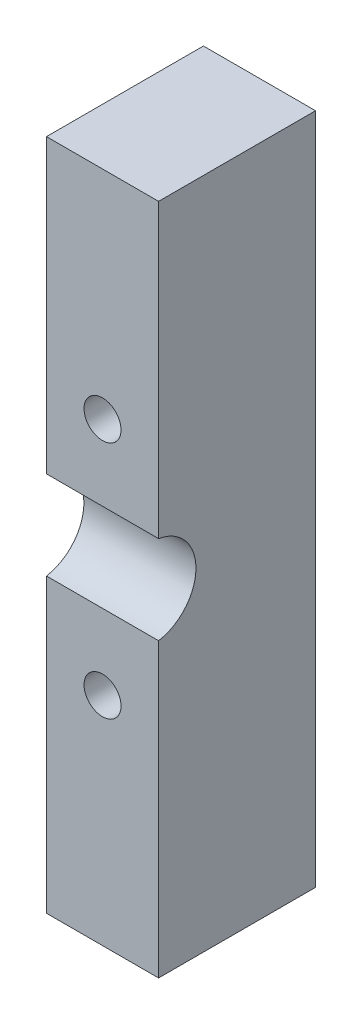
SolidWorks part; units mm, degrees
ref_plane "前视基准面" through (0, 0, 0) normal (0, 0, 1) x (1, 0, 0)
ref_plane "上视基准面" through (0, 0, 0) normal (0, 1, 0) x (1, 0, 0)
ref_plane "右视基准面" through (0, 0, 0) normal (1, 0, 0) x (0, 0, -1)
other "Configuration Table"
sketch "草图1" plane through (0, 0, 0) normal (0, 0, 1) x (1, 0, 0)
  line L0 (0, 0) -> (70, 0)
  line L1 (70, 0) -> (70, 90)
  line L2 (70, 90) -> (0, 90)
  line L3 (0, 90) -> (0, 0)
  dimension "D1" = 70
  dimension "D2" = 90
extrude "凸台-拉伸1" add sketch "草图1" along normal blind 10
sketch "草图2" plane through (0, 0, 10) normal (0, 0, 1) x (1, 0, 0)
  line L0 (70, 0) -> (55, 0)
  line L1 (0, 0) -> (70, 0) construction
  line L2 (55, 0) -> (55, 90)
  line L3 (70, 90) -> (0, 90) construction
  line L4 (55, 90) -> (70, 90)
  line L5 (70, 90) -> (70, 0)
  dimension "D1" = 15
extrude "凸台-拉伸2" add sketch "草图2" along normal blind 12
sketch "草图3" plane through (0, 90, 0) normal (0, 1, 0) x (1, 0, 0)
  line L0 (0, -10) -> (6, -10)
  line L1 (55, -10) -> (0, -10) construction
  line L2 (6, -10) -> (55, -21)
  line L3 (55, -21) -> (55, -10)
  line L4 (55, -10) -> (6, -10)
  line L5 (55, -22) -> (55, -10) construction
  line L6 (70, -22) -> (55, -22) construction
  line M4 (0, -10) -> (55, -10)
  line M5 (55, -10) -> (55, -22)
  dimension "D1" = 6
  dimension "D2" = 1
extrude "凸台-拉伸3" add sketch "草图3" against normal blind 3 contours L2 M4 M5
sketch "草图4" plane through (0, 0, 0) normal (0, -1, 0) x (1, 0, 0)
  line L0 (0, 10) -> (6, 10)
  line L1 (0, 10) -> (55, 10) construction
  line L2 (6, 10) -> (55, 10) construction
  line L3 (6, 10) -> (55, 21)
  line L4 (6, 10) -> (55, 10)
  line L5 (55, 10) -> (55, 21)
  line L6 (55, 10) -> (55, 21) construction
  line L7 (55, 22) -> (70, 22) construction
  line M5 (55, 22) -> (55, 10)
  line M6 (55, 10) -> (0, 10)
  dimension "D1" = 6
  dimension "D2" = 1
extrude "凸台-拉伸4" add sketch "草图4" against normal blind 3 contours L3 M6 M5
sketch "草图5" plane through (0, 0, 22) normal (0, 0, 1) x (1, 0, 0)
  line L0 (70, 45) -> (55, 45) construction
  line L1 (70, 0) -> (70, 90) construction
  line L3 (62.5, 90) -> (62.5, 0) construction
  line L4 (70, 90) -> (55, 90) construction
  line L5 (55, 0) -> (70, 0) construction
  circle A0 centre (62.5, 61) radius 2.475
  circle A1 centre (62.5, 29) radius 2.475
  point P12 (62.5, 61)
  dimension "D2" = 4.95
  dimension "D1" = 16
sketch "草图6" plane through (0, 0, 10) normal (0, 0, 1) x (1, 0, 0)
  line L0 (0, 90) -> (6, 90)
  line L1 (6, 90) -> (6, 0)
  line L2 (0, 90) -> (0, 0)
  line L3 (0, 0) -> (6, 0)
  line L4 (3, 90) -> (3, 0) construction
  line L5 (6, 45) -> (0, 45) construction
  circle A0 centre (3, 61) radius 1.975
  circle A1 centre (3, 29) radius 1.975
  point P12 (0, 45)
  dimension "D2" = 3.95
  dimension "D1" = 29
sketch "草图7" plane through (55, 0, 0) normal (-1, 0, 0) x (0, 0, 1)
  line L0 (22, 45) -> (10, 45) construction
  line L1 (22, 90) -> (22, 0) construction
  circle A0 centre (22, 45) radius 6
  dimension "D1" = 12
extrude "切除-拉伸1" cut sketch "草图7" against normal up to next
extrude "切除-拉伸2" cut sketch "草图5" against normal up to surface (22 mm away) up to face at (35, 45, 0)
extrude "切除-拉伸4" cut sketch "草图6" against normal up to surface (10 mm away) contours A1 | A0 up to face at (64.975, 61, 0)
sketch "草图9" plane through (0, 0, 22) normal (0, 0, 1) x (1, 0, 0)
  line L0 (55, 90) -> (55, 0)
  line L1 (55, 0) -> (70, 0)
  line L2 (70, 0) -> (70, 90)
  line L3 (70, 90) -> (55, 90)
  line L4 (55, 0) -> (70, 0) construction
  dimension "D1" = 15
extrude "切除-拉伸5" cut sketch "草图9" against normal blind 1
sketch "草图10" plane through (0, 0, 0) normal (0, 0, -1) x (-1, 0, 0)
  line L0 (-55, 0) -> (-55, 90) construction
  line L1 (-55, 90) -> (0, 90) construction
  line L2 (0, 90) -> (0, 0) construction
  line L3 (0, 0) -> (-55, 0) construction
sketch "草图11" plane through (0, 0, 0) normal (0, 0, -1) x (-1, 0, 0)
  line L0 (-55, 90) -> (-55, 0)
  line L1 (-55, 0) -> (0, 0)
  line L2 (0, 0) -> (0, 90)
  line L3 (0, 90) -> (-55, 90)
extrude "切除-拉伸6" cut sketch "草图11" against normal through all
